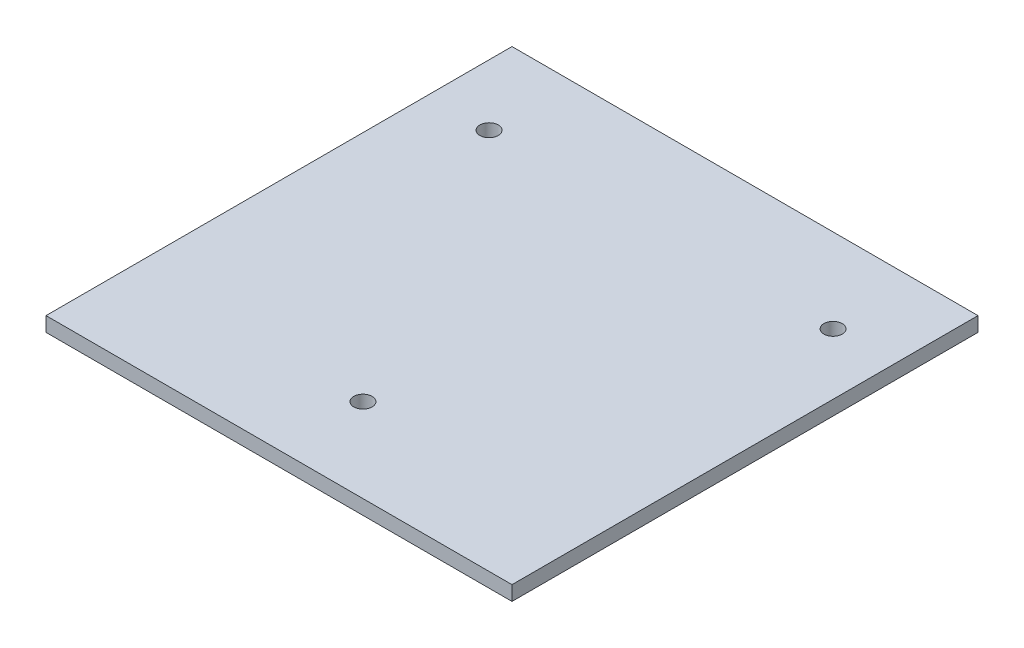
SolidWorks part; units mm, degrees
ref_plane "Plan de face" through (0, 0, 0) normal (0, 0, 1) x (1, 0, 0)
ref_plane "Plan de dessus" through (0, 0, 0) normal (0, 1, 0) x (1, 0, 0)
ref_plane "Plan de droite" through (0, 0, 0) normal (1, 0, 0) x (0, 0, -1)
sketch "Esquisse1" plane through (0, 0, 0) normal (0, 1, 0) x (1, 0, 0)
  line L1 (-101.6, -101.6) -> (101.6, -101.6)
  line L2 (-101.6, -101.6) -> (-101.6, 101.6)
  line L3 (-101.6, 101.6) -> (101.6, 101.6)
  line L4 (101.6, -101.6) -> (101.6, 101.6)
  line L5 (-101.6, -101.6) -> (101.6, 101.6) construction
  line L6 (-101.6, 101.6) -> (101.6, -101.6) construction
  point P0 (0, 0)
  dimension "D1" = 203.2
extrude "Boss.-Extru.1" add sketch "Esquisse1" along normal blind 6.35
sketch "Esquisse2" plane through (0, 6.35, 0) normal (0, 1, 0) x (1, 0, 0)
  circle A0 centre (-75, 65) radius 4
  circle A1 centre (75, 65) radius 4
  circle A2 centre (0, -65) radius 4
  dimension "D1" = 8
  dimension "D2" = 65
  dimension "D3" = 65
  dimension "D4" = 150
  dimension "D5" = 75
extrude "Enlèv. mat.-Extru.1" cut sketch "Esquisse2" against normal through all
